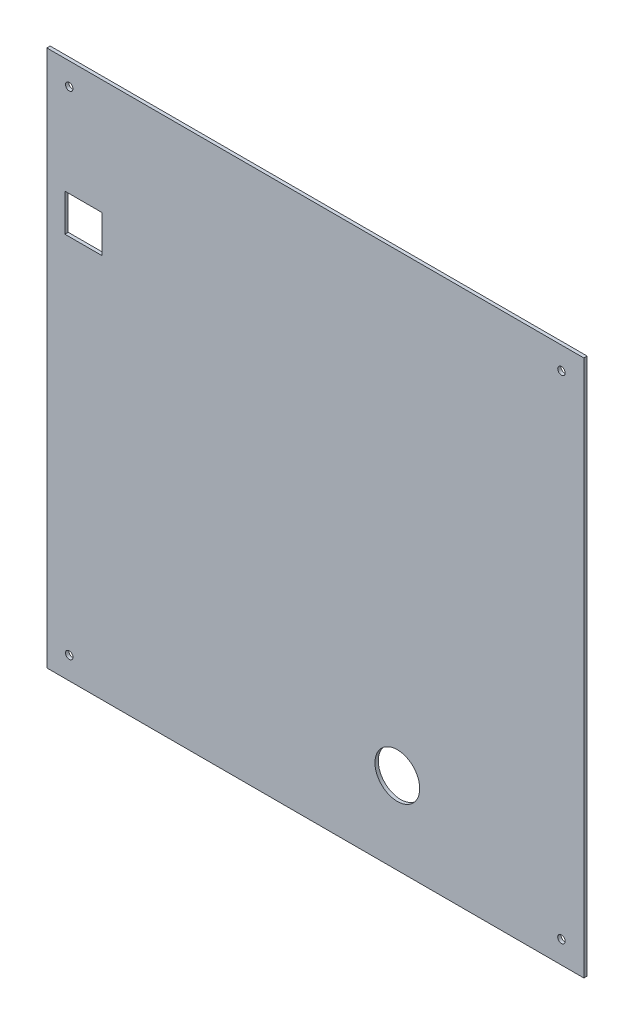
SolidWorks part; units mm, degrees
material "Cedar"
ref_plane "Front Plane" through (0, 0, 0) normal (0, 0, 1) x (1, 0, 0)
ref_plane "Top Plane" through (0, 0, 0) normal (0, 1, 0) x (1, 0, 0)
ref_plane "Right Plane" through (0, 0, 0) normal (1, 0, 0) x (0, 0, -1)
sketch "Sketch1" plane through (0, 0, 0) normal (0, 0, 1) x (1, 0, 0)
  line L1 (-279.4, 0.1905) -> (177.8, 0.1905)
  line L2 (-279.4, 0.1905) -> (-279.4, -457.0095)
  line L3 (-279.4, -457.0095) -> (177.8, -457.0095)
  line L4 (177.8, 0.1905) -> (177.8, -457.0095)
  dimension "D1" = 457.2
  dimension "D2" = 457.2
  dimension "D3" = 177.8
  dimension "D4" = 0.1905
extrude "Boss-Extrude1" add sketch "Sketch1" along normal blind 2.8321
sketch "Sketch2" plane through (0, 0, 2.8321) normal (0, 0, 1) x (1, 0, 0)
  line L0 (177.8, 0.1905) -> (-279.4, 0.1905) construction
  line L1 (-279.4, 0.1905) -> (-279.4, -457.0095) construction
  line L2 (-279.4, -457.0095) -> (177.8, -457.0095) construction
  line L3 (177.8, -457.0095) -> (177.8, 0.1905) construction
  line L4 (-279.4, -457.0095) -> (177.8, -457.0095) construction
  line L5 (-232.283, -97.7265) -> (-264.033, -97.7265)
  line L6 (-232.283, -97.7265) -> (-232.283, -129.4765)
  line L7 (-232.283, -129.4765) -> (-264.033, -129.4765)
  line L8 (-264.033, -97.7265) -> (-264.033, -129.4765)
  line L9 (177.8, -457.0095) -> (177.8, 0.1905) construction
  circle A0 centre (-260.35, -18.8595) radius 3.175
  circle A1 centre (-260.35, -437.9595) radius 3.175
  circle A2 centre (158.75, -437.9595) radius 3.175
  circle A3 centre (158.75, -18.8595) radius 3.175
  circle A4 centre (19.0056, -387.1595) radius 19.05
  point P22 (-264.033, -113.6015)
  dimension "D1" = 6.35
  dimension "D10" = 38.1
  dimension "D2" = 19.05
  dimension "D3" = 19.05
  dimension "D4" = 19.05
  dimension "D5" = 19.05
  dimension "D6" = 31.75
  dimension "D7" = 31.75
  dimension "D8" = 15.367
  dimension "D9" = 97.917
  dimension "D11" = 69.85
  dimension "D12" = 158.7944
extrude "Cut-Extrude1" cut sketch "Sketch2" against normal through all
